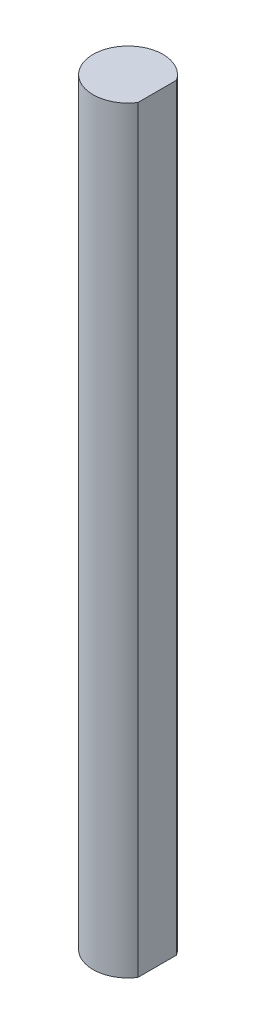
SolidWorks part; units mm, degrees
ref_plane "Front" through (0, 0, 0) normal (0, 0, 1) x (1, 0, 0)
ref_plane "Top" through (0, 0, 0) normal (0, 1, 0) x (1, 0, 0)
ref_plane "Right" through (0, 0, 0) normal (1, 0, 0) x (0, 0, -1)
sketch "Sketch1" plane through (0, 0, 0) normal (0, 1, 0) x (1, 0, 0)
  line L0 (-3, 0) -> (2.5, 0)
  line L1 (2.5, 0) -> (2.5, 1.6583)
  line L2 (2.5, 1.6583) -> (2.5, -1.6583)
  circle A0 centre (0, 0) radius 3
  dimension "D1" = 5.5
extrude "Boss-Extrude1" add sketch "Sketch1" along normal blind 65 contours L1 A0 L0 | L0 A0 L2
